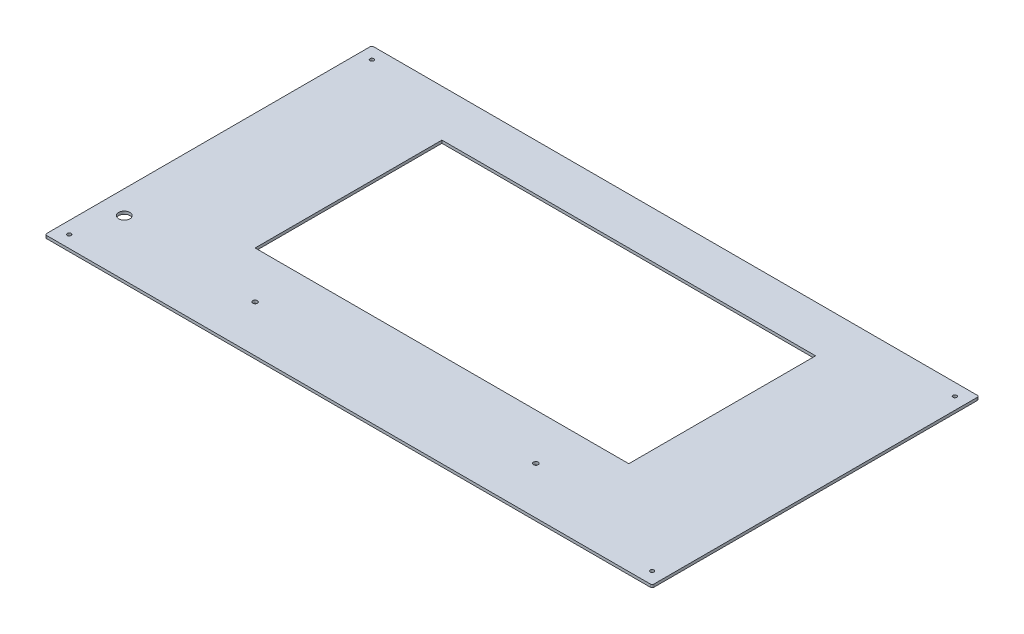
SolidWorks part; units mm, degrees
ref_plane "前视基准面" through (0, 0, 0) normal (0, 0, 1) x (1, 0, 0)
ref_plane "上视基准面" through (0, 0, 0) normal (0, 1, 0) x (1, 0, 0)
ref_plane "右视基准面" through (0, 0, 0) normal (1, 0, 0) x (0, 0, -1)
sketch "草图1" plane through (0, 0, 0) normal (0, 1, 0) x (1, 0, 0)
  line L1 (2, 0) -> (648, 0)
  line L2 (0, 2) -> (0, 348)
  line L3 (2, 350) -> (648, 350)
  line L4 (650, 2) -> (650, 348)
  line L5 (525, 100) -> (125, 100)
  line L6 (525, 100) -> (525, 300)
  line L7 (525, 300) -> (125, 300)
  line L8 (125, 100) -> (125, 300)
  arc A0 (648, 350) -> (650, 348) centre (648, 348) cw
  arc A1 (648, 0) -> (650, 2) centre (648, 2) ccw
  arc A2 (2, 0) -> (0, 2) centre (2, 2) cw
  arc A3 (2, 350) -> (0, 348) centre (2, 348) ccw
  circle A4 centre (13, 13) radius 2
  circle A5 centre (637, 13) radius 2
  circle A6 centre (13, 337) radius 2
  circle A7 centre (637, 337) radius 2
  circle A8 centre (475, 50.4926) radius 2.5
  circle A9 centre (175, 50) radius 2.5
  circle A10 centre (25, 60) radius 6
  point P9 (650, 0)
  point P12 (0, 0)
  point P15 (0, 350)
  dimension "D3" = 2
  dimension "D4" = 4
  dimension "D7" = 4
  dimension "D10" = 4
  dimension "D13" = 4
  dimension "D20" = 5
  dimension "D23" = 5
  dimension "D26" = 12
  dimension "D1" = 350
  dimension "D2" = 650
  dimension "D5" = 13
  dimension "D6" = 13
  dimension "D8" = 13
  dimension "D9" = 13
  dimension "D11" = 13
  dimension "D12" = 13
  dimension "D14" = 13
  dimension "D15" = 13
  dimension "D16" = 400
  dimension "D17" = 200
  dimension "D18" = 125
  dimension "D19" = 50
  dimension "D21" = 50.4926
  dimension "D22" = 175
  dimension "D24" = 300
  dimension "D25" = 50
  dimension "D27" = 60
  dimension "D28" = 25
extrude "凸台-拉伸1" add sketch "草图1" against normal blind 3
